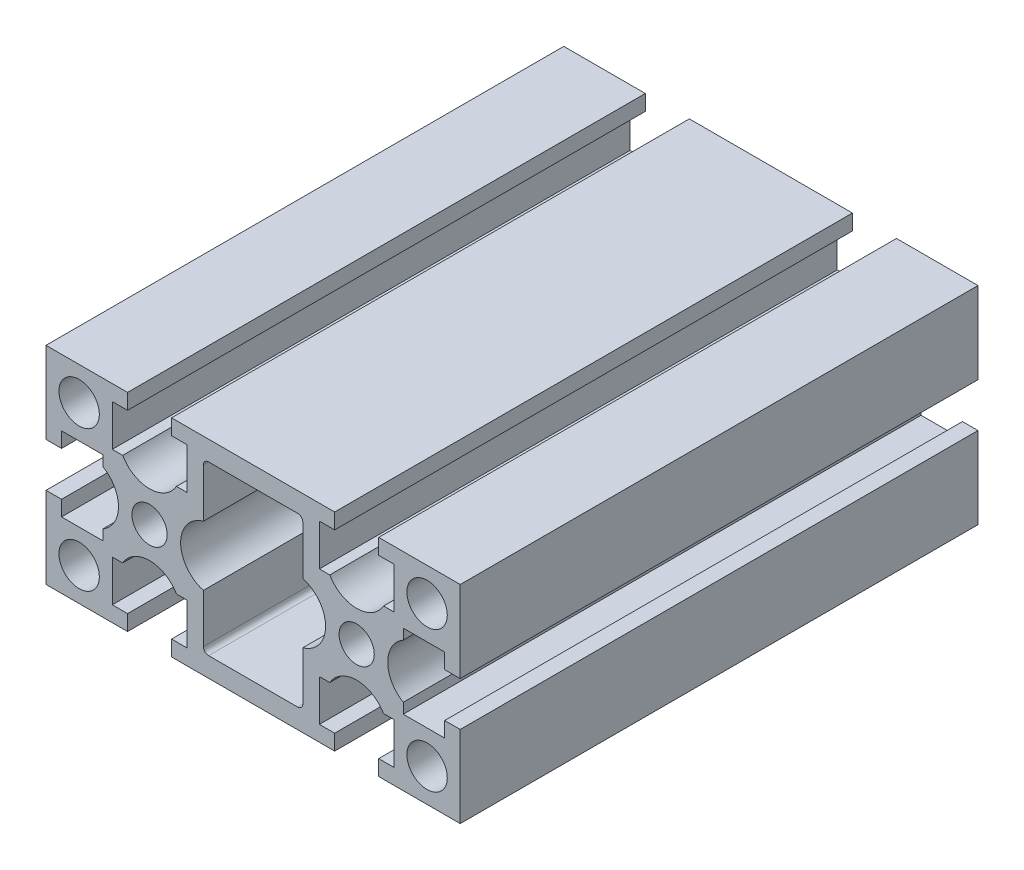
SolidWorks part; units mm, degrees
ref_plane "前视基准面" through (0, 0, 0) normal (0, 0, 1) x (1, 0, 0)
ref_plane "上视基准面" through (0, 0, 0) normal (0, 1, 0) x (1, 0, 0)
ref_plane "右视基准面" through (0, 0, 0) normal (1, 0, 0) x (0, 0, -1)
sketch "草图1" plane through (0, 0, 0) normal (0, 0, 1) x (1, 0, 0)
  line L0 (-24.7328, 19.8486) -> (-40.4828, 19.8486)
  line L1 (-40.4828, 19.8486) -> (-40.4828, 4.0986)
  line L2 (-24.7328, 16.8486) -> (-27.6828, 16.8486)
  line L3 (-37.4828, 7.0486) -> (-37.4828, 4.0986)
  line L4 (-29.4828, 7.0486) -> (-29.4828, 5.0447)
  line L5 (-25.679, 8.8486) -> (-27.6828, 8.8486)
  line L6 (-37.4828, 7.0486) -> (-29.4828, 7.0486)
  line L7 (-40.4828, 4.0986) -> (-37.4828, 4.0986)
  line L8 (-27.6828, 16.8486) -> (-27.6828, 8.8486)
  line L9 (-24.7328, 19.8486) -> (-24.7328, 16.8486)
  line L10 (-16.2328, 19.8486) -> (-0.4828, 19.8486)
  line L11 (-16.2328, 16.8486) -> (-13.2828, 16.8486)
  line L12 (-15.2867, 8.8486) -> (-13.2828, 8.8486)
  line L13 (-13.2828, 16.8486) -> (-13.2828, 8.8486)
  line L14 (-10.0828, 15.0486) -> (-10.0828, 5.6313)
  line L15 (-16.2328, 19.8486) -> (-16.2328, 16.8486)
  line L16 (-24.7328, -20.1514) -> (-40.4828, -20.1514)
  line L17 (-40.4828, -20.1514) -> (-40.4828, -4.4014)
  line L18 (-24.7328, -17.1514) -> (-27.6828, -17.1514)
  line L19 (-37.4828, -7.3514) -> (-37.4828, -4.4014)
  line L20 (-29.4828, -7.3514) -> (-29.4828, -5.3476)
  line L21 (-25.679, -9.1514) -> (-27.6828, -9.1514)
  line L22 (-37.4828, -7.3514) -> (-29.4828, -7.3514)
  line L23 (-40.4828, -4.4014) -> (-37.4828, -4.4014)
  line L24 (-27.6828, -17.1514) -> (-27.6828, -9.1514)
  line L25 (-24.7328, -20.1514) -> (-24.7328, -17.1514)
  line L26 (-16.2328, -20.1514) -> (-0.4828, -20.1514)
  line L27 (-16.2328, -17.1514) -> (-13.2828, -17.1514)
  line L28 (-15.2867, -9.1514) -> (-13.2828, -9.1514)
  line L29 (-13.2828, -17.1514) -> (-13.2828, -9.1514)
  line L30 (-16.2328, -20.1514) -> (-16.2328, -17.1514)
  line L31 (15.2672, 19.8486) -> (-0.4828, 19.8486)
  line L32 (15.2672, 16.8486) -> (12.3172, 16.8486)
  line L33 (14.321, 8.8486) -> (12.3172, 8.8486)
  line L34 (12.3172, 16.8486) -> (12.3172, 8.8486)
  line L35 (9.1172, 15.0486) -> (9.1172, 5.6313)
  line L36 (15.2672, 19.8486) -> (15.2672, 16.8486)
  line L37 (23.7672, 19.8486) -> (39.5172, 19.8486)
  line L38 (39.5172, 19.8486) -> (39.5172, 4.0986)
  line L39 (23.7672, 16.8486) -> (26.7172, 16.8486)
  line L40 (36.5172, 7.0486) -> (36.5172, 4.0986)
  line L41 (28.5172, 7.0486) -> (28.5172, 5.0447)
  line L42 (24.7133, 8.8486) -> (26.7172, 8.8486)
  line L43 (36.5172, 7.0486) -> (28.5172, 7.0486)
  line L44 (39.5172, 4.0986) -> (36.5172, 4.0986)
  line L45 (26.7172, 16.8486) -> (26.7172, 8.8486)
  line L46 (23.7672, 19.8486) -> (23.7672, 16.8486)
  line L47 (15.2672, -20.1514) -> (-0.4828, -20.1514)
  line L48 (15.2672, -17.1514) -> (12.3172, -17.1514)
  line L49 (14.321, -9.1514) -> (12.3172, -9.1514)
  line L50 (12.3172, -17.1514) -> (12.3172, -9.1514)
  line L51 (15.2672, -20.1514) -> (15.2672, -17.1514)
  line L52 (23.7672, -20.1514) -> (39.5172, -20.1514)
  line L53 (39.5172, -20.1514) -> (39.5172, -4.4014)
  line L54 (23.7672, -17.1514) -> (26.7172, -17.1514)
  line L55 (36.5172, -7.3514) -> (36.5172, -4.4014)
  line L56 (28.5172, -7.3514) -> (28.5172, -5.3476)
  line L57 (24.7133, -9.1514) -> (26.7172, -9.1514)
  line L58 (36.5172, -7.3514) -> (28.5172, -7.3514)
  line L59 (39.5172, -4.4014) -> (36.5172, -4.4014)
  line L60 (26.7172, -17.1514) -> (26.7172, -9.1514)
  line L61 (23.7672, -20.1514) -> (23.7672, -17.1514)
  line L62 (-9.0828, 16.0486) -> (8.1172, 16.0486)
  line L63 (-10.0828, -15.3514) -> (-10.0828, -5.9341)
  line L64 (9.1172, -15.3514) -> (9.1172, -5.9341)
  line L65 (-9.0828, -16.3514) -> (8.1172, -16.3514)
  circle A0 centre (-34.0828, 13.4486) radius 3.9
  arc A1 (-9.0828, 16.0486) -> (-10.0828, 15.0486) centre (-9.0828, 15.0486) ccw
  circle A2 centre (-34.0828, -13.7514) radius 3.9
  circle A3 centre (-20.4828, -0.1514) radius 3.4
  arc A4 (-29.4828, -5.3476) -> (-29.4828, 5.0447) centre (-32.4828, -0.1514) ccw
  arc A5 (-10.0828, 5.6313) -> (-10.0828, -5.9341) centre (-8.4828, -0.1514) ccw
  arc A6 (-25.679, 8.8486) -> (-15.2867, 8.8486) centre (-20.4828, 11.8486) ccw
  arc A7 (-15.2867, -9.1514) -> (-25.679, -9.1514) centre (-20.4828, -12.1514) ccw
  arc A8 (9.1172, 15.0486) -> (8.1172, 16.0486) centre (8.1172, 15.0486) ccw
  circle A9 centre (33.1172, 13.4486) radius 3.9
  circle A10 centre (33.1172, -13.7514) radius 3.9
  circle A11 centre (19.5172, -0.1514) radius 3.4
  arc A12 (9.1172, -5.9341) -> (9.1172, 5.6313) centre (7.5172, -0.1514) ccw
  arc A13 (28.5172, 5.0447) -> (28.5172, -5.3476) centre (31.5172, -0.1514) ccw
  arc A14 (14.321, 8.8486) -> (24.7133, 8.8486) centre (19.5172, 11.8486) ccw
  arc A15 (24.7133, -9.1514) -> (14.321, -9.1514) centre (19.5172, -12.1514) ccw
  arc A16 (-10.0828, -15.3514) -> (-9.0828, -16.3514) centre (-9.0828, -15.3514) ccw
  arc A18 (8.1172, -16.3514) -> (9.1172, -15.3514) centre (8.1172, -15.3514) ccw
extrude "凸台-拉伸1" add sketch "草图1" along normal blind 100
